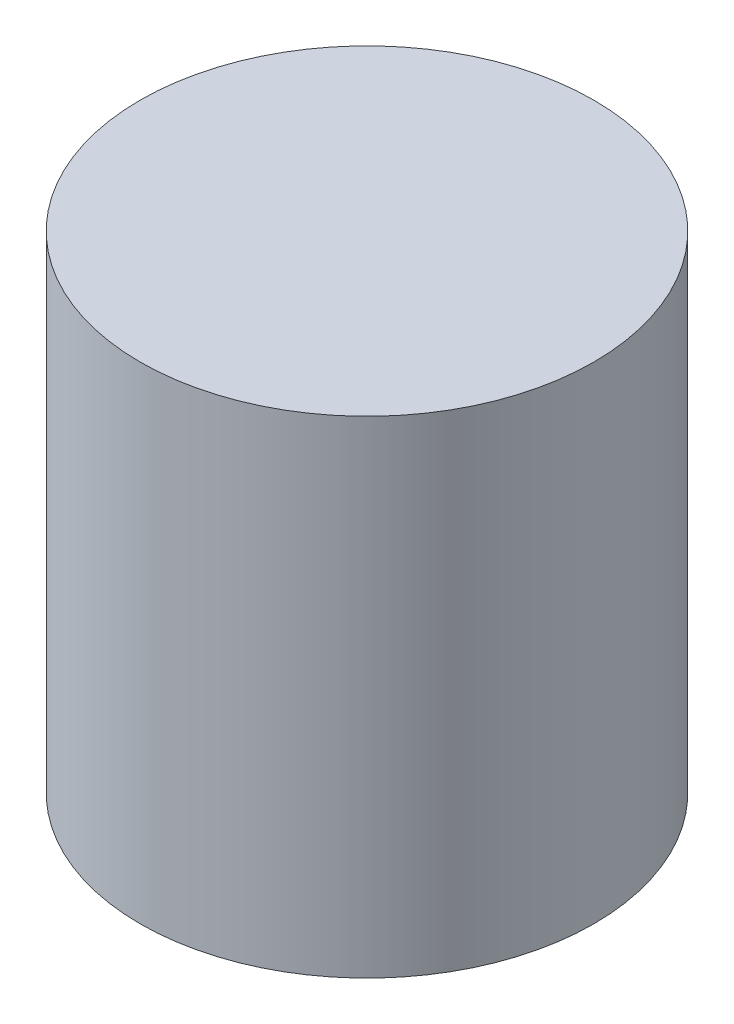
SolidWorks part; units mm, degrees
ref_plane "Front Plane" through (0, 0, 0) normal (0, 0, 1) x (1, 0, 0)
ref_plane "Top Plane" through (0, 0, 0) normal (0, 1, 0) x (1, 0, 0)
ref_plane "Right Plane" through (0, 0, 0) normal (1, 0, 0) x (0, 0, -1)
sketch "Sketch1" plane through (0, 0, 0) normal (0, 0, 1) x (1, 0, 0)
  line L0 (0, 200) -> (25.4, 200)
  line L2 (0, 200) -> (0, 254.4797)
  line L3 (0, 254.4797) -> (25.4, 254.4797)
  line L4 (25.4, 200) -> (25.4, 254.4797)
  point P4 (0, 0)
revolve "Revolve1" add sketch "Sketch1" angle 360 about L2
